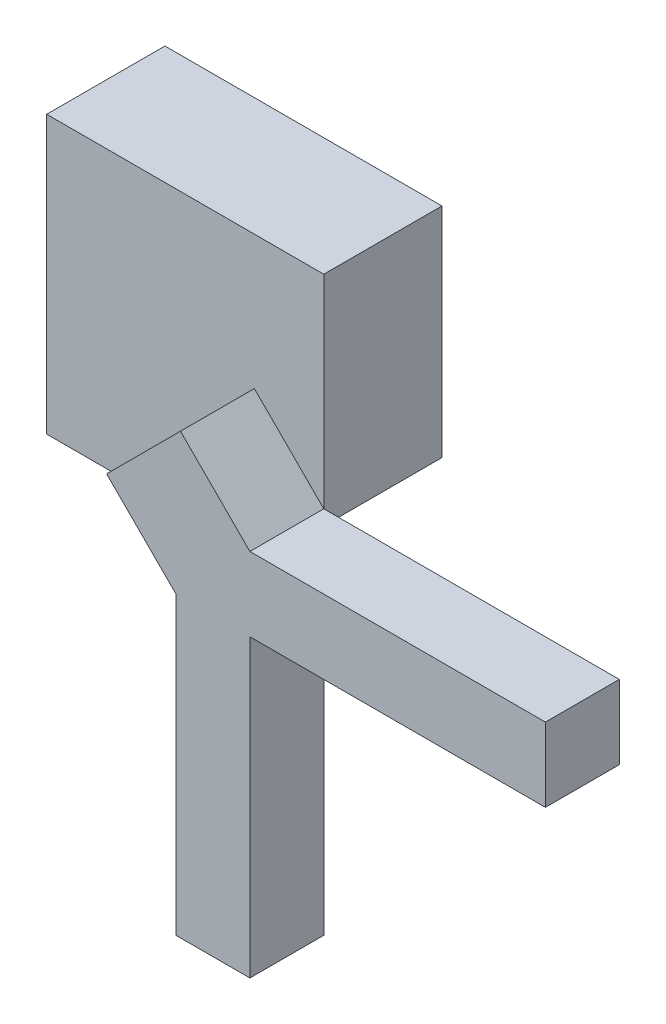
SolidWorks part; units mm, degrees
ref_plane "Front Plane" through (0, 0, 0) normal (0, 0, 1) x (1, 0, 0)
ref_plane "Top Plane" through (0, 0, 0) normal (0, 1, 0) x (1, 0, 0)
ref_plane "Right Plane" through (0, 0, 0) normal (1, 0, 0) x (0, 0, -1)
sketch "Sketch1" plane through (0, 0, 0) normal (0, 0, 1) x (1, 0, 0)
  line L0 (9.375, -4.375) -> (9.375, -9.375)
  line L1 (-9.375, 9.375) -> (9.375, 9.375)
  line L2 (-9.375, 9.375) -> (-9.375, -9.375)
  line L3 (-9.375, -9.375) -> (4.375, -9.375)
  line L4 (9.375, 9.375) -> (9.375, -4.375)
  line L5 (-9.375, 9.375) -> (9.375, -9.375) construction
  line L6 (-9.375, -9.375) -> (9.375, 9.375) construction
  line L8 (9.375, -9.375) -> (9.375, -29.375) construction
  line L9 (9.375, -29.375) -> (4.375, -29.375) construction
  line L10 (4.375, -9.375) -> (4.375, -29.375) construction
  line L11 (9.375, -9.375) -> (29.375, -9.375) construction
  line L13 (9.375, -4.375) -> (29.375, -4.375) construction
  line L14 (29.375, -9.375) -> (29.375, -4.375) construction
  line L15 (4.375, -9.375) -> (9.375, -9.375)
  point P0 (0, 0)
  dimension "D1" = 18.75
  dimension "D2" = 18.75
  dimension "D3" = 5
  dimension "D4" = 5
  dimension "D5" = 20
  dimension "D6" = 20
extrude "Boss-Extrude1" add sketch "Sketch1" along normal blind 8
sketch "Sketch3" plane through (0, 0, 0) normal (0, 0, 1) x (1, 0, 0)
  line L0 (4.375, -9.375) -> (4.375, -29.375)
  line L1 (4.375, -29.375) -> (9.375, -29.375)
  line L2 (9.375, -29.375) -> (9.375, -9.375)
  line L3 (9.375, -9.375) -> (29.375, -9.375)
  line L4 (29.375, -9.375) -> (29.375, -4.375)
  line L5 (29.375, -4.375) -> (9.375, -4.375)
  line L7 (-0.3229, -4.6771) -> (4.6771, 0.3229)
  line L9 (4.375, -9.375) -> (-0.3229, -4.6771)
  line L10 (9.375, -4.375) -> (4.6771, 0.3229)
  dimension "D1" = 135
extrude "Boss-Extrude2" add sketch "Sketch3" along normal blind 5 from surface at 8 starting at face at (0, 0, 8)
sketch "Sketch5" plane through (0, 0, 0) normal (0, 0, 1) x (1, 0, 0)
  line L1 (9.375, -9.375) -> (5.375, -9.375)
  line L2 (9.375, -9.375) -> (9.375, -5.375)
  line L3 (9.375, -5.375) -> (5.375, -5.375)
  line L4 (5.375, -9.375) -> (5.375, -5.375)
  dimension "D1" = 4
  dimension "D2" = 4
extrude "Cut-Extrude1" cut sketch "Sketch5" along normal up to surface (8 mm away) up to face at (19.375, -6.875, 8)
